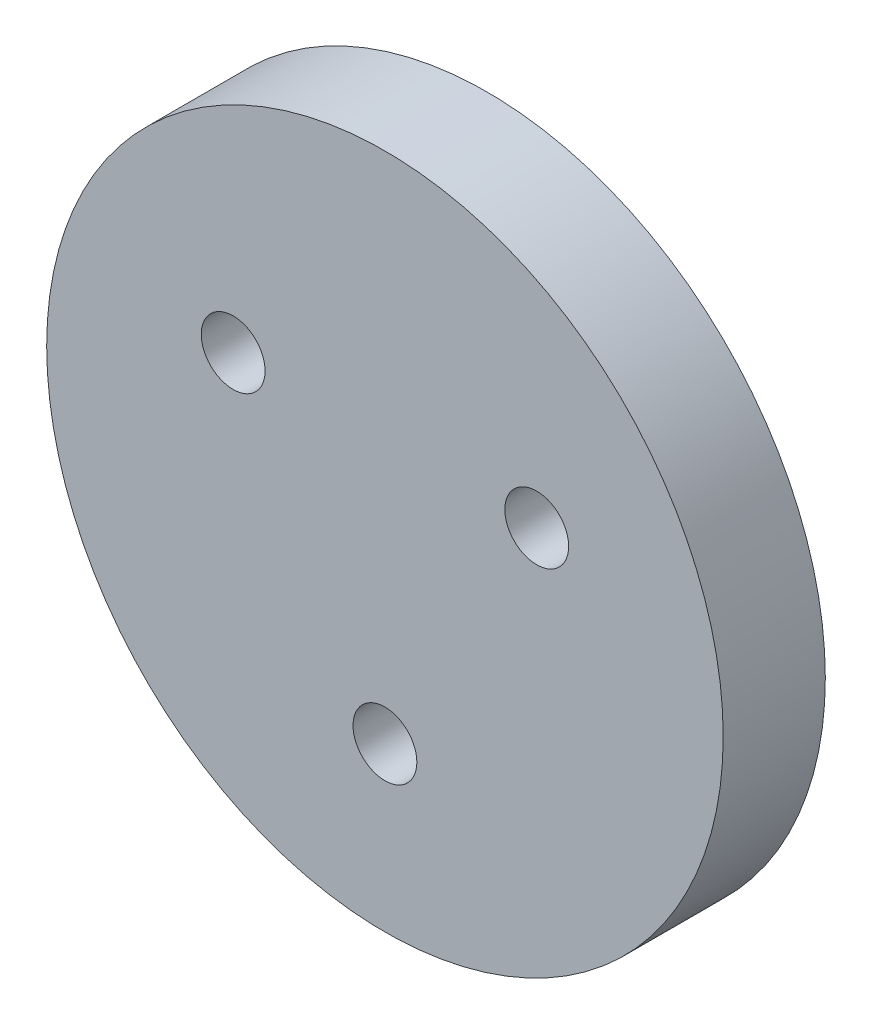
SolidWorks part; units mm, degrees
ref_plane "Front Plane" through (0, 0, 0) normal (0, 0, 1) x (1, 0, 0)
ref_plane "Top Plane" through (0, 0, 0) normal (0, 1, 0) x (1, 0, 0)
ref_plane "Right Plane" through (0, 0, 0) normal (1, 0, 0) x (0, 0, -1)
sketch "Sketch1" plane through (0, 0, 0) normal (0, 0, 1) x (1, 0, 0)
  line L0 (0, 0) -> (0, -26.5) construction
  circle A0 centre (0, 0) radius 26.5
  circle A1 centre (0, 0) radius 4.555 construction
  circle A2 centre (0, -13.73) radius 9.175 construction
  circle A3 centre (0, -13.73) radius 2.5
  circle A4 centre (-11.8905, 6.865) radius 2.5
  circle A5 centre (11.8905, 6.865) radius 2.5
  point P14 (0, 0)
  dimension "D1" = 53
  dimension "D2" = 9.11
  dimension "D3" = 18.35
  dimension "D4" = 5
  dimension "D5" = 3
extrude "Boss-Extrude1" add sketch "Sketch1" along normal blind 8
